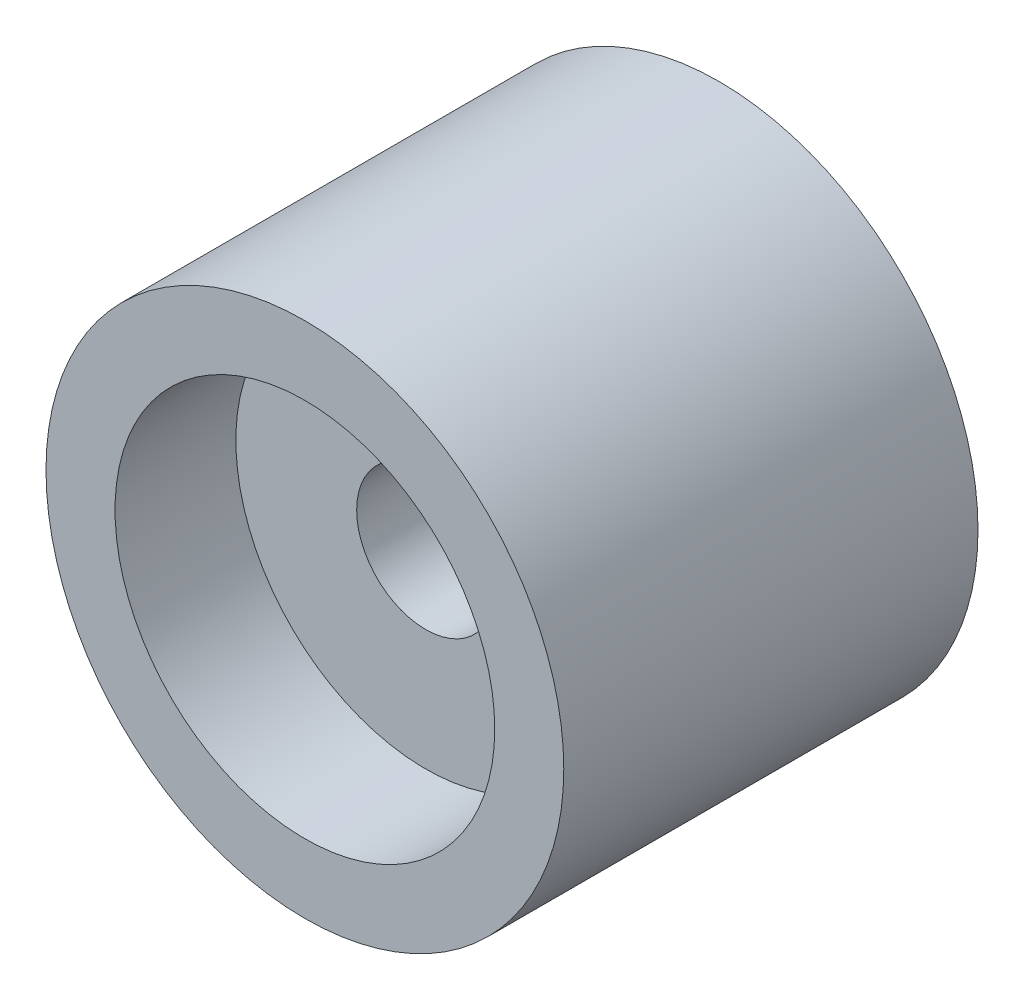
SolidWorks part; units mm, degrees
material "Nylon 6/10"
ref_plane "Front Plane" through (0, 0, 0) normal (0, 0, 1) x (1, 0, 0)
ref_plane "Top Plane" through (0, 0, 0) normal (0, 1, 0) x (1, 0, 0)
ref_plane "Right Plane" through (0, 0, 0) normal (1, 0, 0) x (0, 0, -1)
sketch "Sketch1" plane through (0, 0, 0) normal (0, 0, 1) x (1, 0, 0)
  circle A0 centre (0, 0) radius 15
  circle A1 centre (0, 0) radius 4
  dimension "D1" = 30
  dimension "D2" = 8
extrude "Extrude1" add sketch "Sketch1" along normal blind 24
sketch "Sketch2" plane through (0, 0, 24) normal (0, 0, 1) x (1, 0, 0)
  circle A0 centre (0, 0) radius 11
  dimension "D2" = 22
extrude "Cut-Extrude1" cut sketch "Sketch2" against normal blind 7
sketch "Sketch3" plane through (0, 0, 0) normal (0, 0, -1) x (-1, 0, 0)
  circle A0 centre (0, 0) radius 11
  dimension "D2" = 22
extrude "Cut-Extrude2" cut sketch "Sketch3" against normal blind 7
